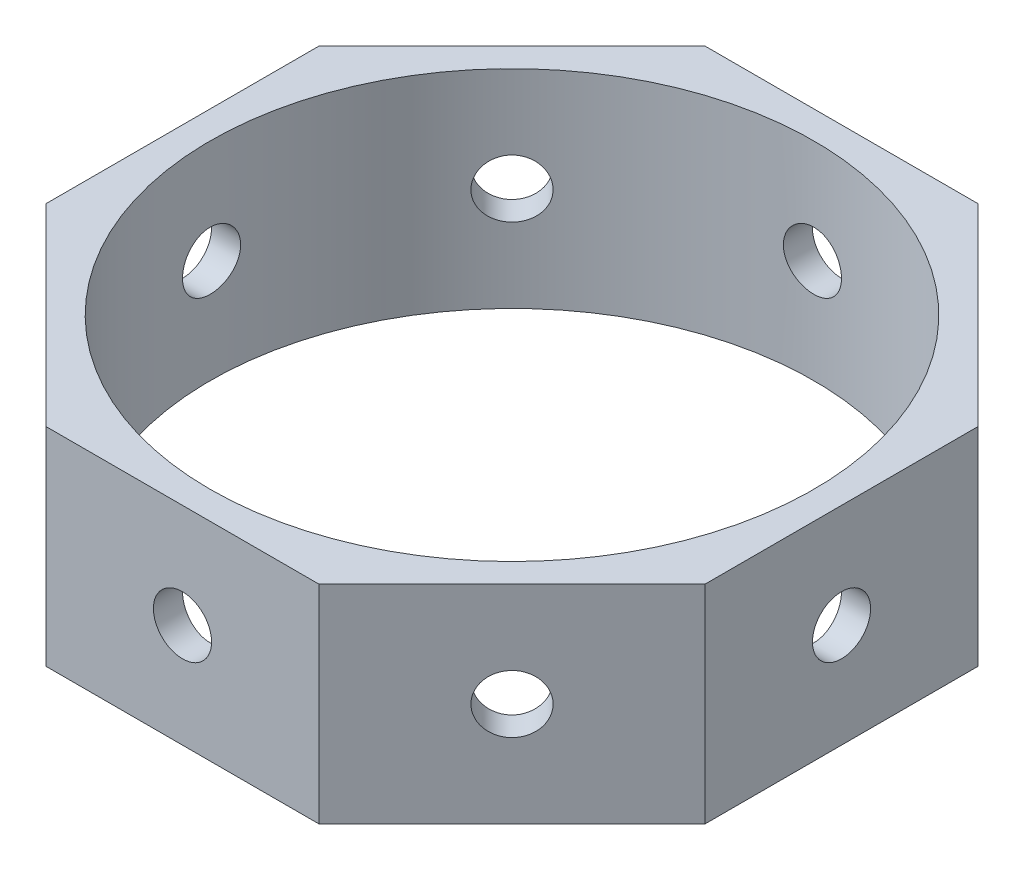
SolidWorks part; units mm, degrees
ref_plane "Front Plane" through (0, 0, 0) normal (0, 0, 1) x (1, 0, 0)
ref_plane "Top Plane" through (0, 0, 0) normal (0, 1, 0) x (1, 0, 0)
ref_plane "Right Plane" through (0, 0, 0) normal (1, 0, 0) x (0, 0, -1)
sketch "Sketch1" plane through (0, 0, 0) normal (0, 1, 0) x (1, 0, 0)
  line L1 (12.52, 30.226) -> (-12.52, 30.226)
  line L2 (-12.52, 30.226) -> (-30.226, 12.52)
  line L3 (-30.226, 12.52) -> (-30.226, -12.52)
  line L4 (-30.226, -12.52) -> (-12.52, -30.226)
  line L5 (-12.52, -30.226) -> (12.52, -30.226)
  line L6 (12.52, -30.226) -> (30.226, -12.52)
  line L7 (30.226, -12.52) -> (30.226, 12.52)
  line L8 (30.226, 12.52) -> (12.52, 30.226)
  line L9 (0, 30.226) -> (0, 0) construction
  circle A1 centre (0, 0) radius 27.686
  circle A2 centre (0, 0) radius 30.226 construction
  point P3 (0, 0)
  point P5 (0, 27.686)
  point P8 (0, 0)
  dimension "D1" = 55.372
  dimension "D2" = 2.54
  dimension "D3" = 60.452
extrude "Boss-Extrude1" add sketch "Sketch1" along normal blind 19.05
sketch "Sketch2" plane through (0, 0, 30.226) normal (0, 0, 1) x (1, 0, 0)
  line L0 (0, 0) -> (0, 19.05) construction
  line L1 (-12.52, 19.05) -> (12.52, 19.05) construction
  circle A0 centre (0, 9.525) radius 2.667
  point P5 (0, 6.9574)
  point P8 (0, 2.9088)
  point P9 (0, 9.525)
  dimension "D1" = 5.334
extrude "Cut-Extrude1" cut sketch "Sketch2" against normal up to next
pattern_circular "CirPattern1" count 8 over 360 about axis through (0, 19.05, 0) along (0, 1, 0) of "Cut-Extrude1"
